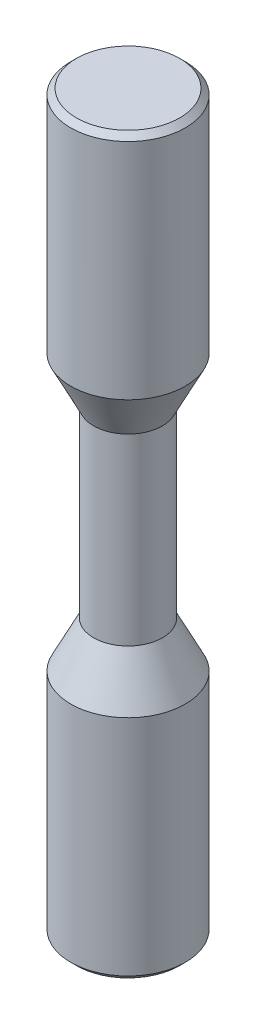
SolidWorks part; units mm, degrees
ref_plane "Front Plane" through (0, 0, 0) normal (0, 0, 1) x (1, 0, 0)
ref_plane "Top Plane" through (0, 0, 0) normal (0, 1, 0) x (1, 0, 0)
ref_plane "Right Plane" through (0, 0, 0) normal (1, 0, 0) x (0, 0, -1)
sketch "Sketch1" plane through (0, 0, 0) normal (0, 0, 1) x (1, 0, 0)
  line L0 (0, 0) -> (0, 101.6)
  line L1 (0, 101.6) -> (7.9375, 101.6)
  line L2 (7.9375, 101.6) -> (7.9375, 69.85)
  line L3 (7.9375, 69.85) -> (4.7625, 63.5)
  line L4 (4.7625, 63.5) -> (4.7625, 38.1)
  line L5 (4.7625, 38.1) -> (7.9375, 31.75)
  line L6 (7.9375, 31.75) -> (7.9375, 0)
  line L7 (7.9375, 0) -> (0, 0)
  point P4 (4.641, 46.804)
  point P10 (3.8209, 42.7034)
  point P11 (4.8804, 25.521)
  point P12 (10.2478, 57.15)
  dimension "D1" = 7.9375
  dimension "D2" = 101.6
  dimension "D3" = 31.75
  dimension "D4" = 31.75
  dimension "D5" = 25.4
  dimension "D6" = 3.175
  dimension "D7" = 6.35
  dimension "D8" = 3.175
revolve "Revolve1" add sketch "Sketch1" angle 360 about L0
chamfer "Chamfer1" distance 0.7937 angle 45 2 edges at (0, 0, -7.9375) (0, 101.6, -7.9375)
